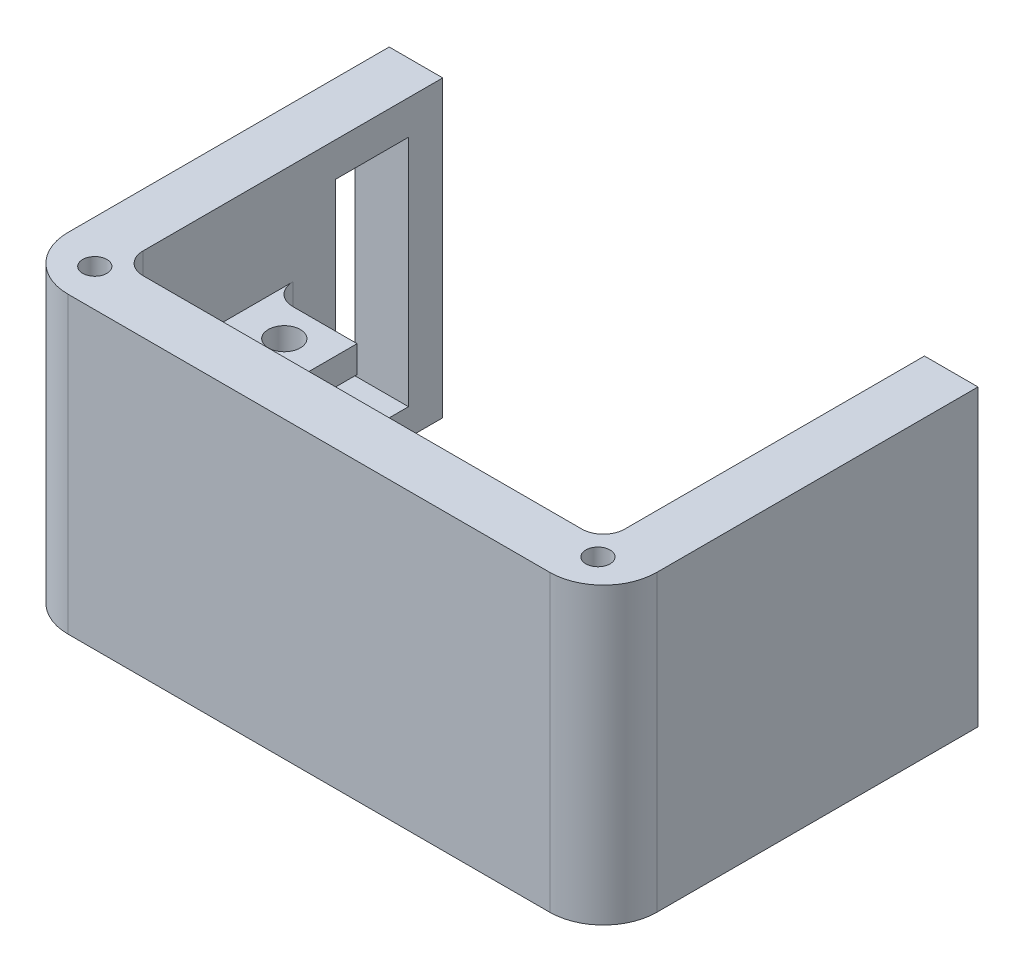
SolidWorks part; units mm, degrees
ref_plane "Front Plane" through (0, 0, 0) normal (0, 0, 1) x (1, 0, 0)
ref_plane "Top Plane" through (0, 0, 0) normal (0, 1, 0) x (1, 0, 0)
ref_plane "Right Plane" through (0, 0, 0) normal (1, 0, 0) x (0, 0, -1)
sketch "Sketch1" plane through (0, 0, 0) normal (0, 1, 0) x (1, 0, 0)
  line L0 (0, -55) -> (0, 55) construction
  line L1 (-34.925, -15.875) -> (34.925, -15.875)
  line L2 (-34.925, -15.875) -> (-34.925, 15.875)
  line L3 (-34.925, 15.875) -> (34.925, 15.875) construction
  line L4 (34.925, -15.875) -> (34.925, 15.875)
  line L5 (-34.925, -15.875) -> (34.925, 15.875) construction
  line L6 (-34.925, 15.875) -> (34.925, -15.875) construction
  line L7 (28.575, 15.875) -> (-28.575, 15.875) construction
  line L8 (28.575, 15.875) -> (28.575, -9.525)
  line L9 (28.575, -9.525) -> (-28.575, -9.525)
  line L10 (-28.575, 15.875) -> (-28.575, -9.525)
  line L11 (28.575, 15.875) -> (-28.575, -9.525) construction
  line L12 (28.575, -9.525) -> (-28.575, 15.875) construction
  line L13 (-28.575, 15.875) -> (-34.925, 15.875)
  line L14 (34.925, 15.875) -> (34.925, 28.575)
  line L15 (34.925, 28.575) -> (28.575, 28.575)
  line L16 (28.575, 28.575) -> (28.575, 15.875)
  point P0 (0, 0)
  point P6 (0, 3.175)
  point P11 (0, -9.525)
  dimension "D1" = 31.75
  dimension "D2" = 69.85
  dimension "D3" = 57.15
  dimension "D4" = 25.4
  dimension "D5" = 44.45
extrude "Boss-Extrude1" add sketch "Sketch1" along normal blind 31.75 contours L10 L3 L2 L1 L4 L8 L9
sketch "Sketch5" plane through (-28.575, 0, 0) normal (1, 0, 0) x (0, 0, -1)
  line L1 (0.635, 16.51) -> (8.255, 16.51)
  line L2 (0.635, 16.51) -> (0.635, 19.685)
  line L3 (0.635, 19.685) -> (8.255, 19.685)
  line L4 (8.255, 16.51) -> (8.255, 19.685)
  line L5 (0.635, 16.51) -> (8.255, 19.685) construction
  line L6 (0.635, 19.685) -> (8.255, 16.51) construction
  line L8 (15.875, 31.75) -> (-9.525, 31.75) construction
  line L10 (15.875, 31.75) -> (15.875, 0) construction
  point P0 (4.445, 18.0975)
  dimension "D1" = 7.62
  dimension "D2" = 3.175
  dimension "D3" = 15.24
  dimension "D4" = 7.62
extrude "Boss-Extrude2" add sketch "Sketch5" along normal blind 10.16 contours L3 L4 L1 L2
sketch "Sketch7" plane through (0, 19.685, 0) normal (0, 1, 0) x (1, 0, 0)
  line L1 (-28.575, 0.635) -> (-28.575, 8.255) construction
  line L3 (-18.415, 0.635) -> (-28.575, 0.635) construction
  point P0 (-23.241, 4.445)
  dimension "D1" = 3.81
  dimension "D2" = 5.334
hole_wizard "#6 Clearance Hole1" positions "Sketch8" profile "Sketch10" hole size "#6" standard "ANSI Inch" end condition up to next
sketch "Sketch8" plane through (0, 19.685, 0) normal (0, 1, 0) x (1, 0, 0)
  point P0 (-23.241, 4.445)
sketch "Sketch10" plane through (-23.241, 19.685, -4.445) normal (1, 0, 0) x (0, 0, 1)
  line L0 (0, 0) -> (0, 3.175)
  line L1 (0, 3.175) -> (1.8986, 3.175)
  line L2 (1.8986, 3.175) -> (1.8986, 0)
  line L5 (1.8986, 0) -> (0, 0)
  line L11 (0, -6.35) -> (0, 107.95) construction
  dimension "Thru Hole Dia." = 3.7973
  dimension "Thru Hole Depth" = 3.175
mirror "Mirror4" about plane through (0, 0, 0) normal (1, 0, 0) of "#6 Clearance Hole1", "Boss-Extrude2"
sketch "Sketch11" plane through (0, 0, 0) normal (0, -1, 0) x (1, 0, 0)
  line L5 (-28.575, -15.875) -> (-28.575, 9.525) construction
  line L7 (-34.925, 15.875) -> (-34.925, -15.875) construction
  line L13 (-28.575, -28.575) -> (-28.575, 9.525)
  line L15 (-34.925, 15.875) -> (-34.925, -28.575)
  line L17 (-34.925, -28.575) -> (-28.575, -28.575)
  line L18 (-28.575, -15.875) -> (-34.925, -15.875) construction
  line L19 (-28.575, 9.525) -> (28.575, 9.525)
  line L20 (28.575, 9.525) -> (28.575, -28.575)
  line L21 (28.575, -28.575) -> (34.925, -28.575)
  line L22 (34.925, -28.575) -> (34.925, 15.875)
  line L23 (34.925, 15.875) -> (-34.925, 15.875)
  dimension "D1" = 12.7
extrude "Boss-Extrude3" add sketch "Sketch11" along normal blind 3.175 contours L15 L17 L13 L19 L20 L21 L22 L23
sketch "Sketch12" [suppressed] plane through (0, 0, 0) normal (0, 1, 0) x (1, 0, 0)
  line L0 (-28.575, 28.575) -> (-28.575, 15.875) construction
  line L1 (-34.925, 28.575) -> (-28.575, 28.575)
  line L2 (-34.925, 28.575) -> (-34.925, 24.511)
  line L3 (-34.925, 24.511) -> (-28.575, 24.511)
  line L4 (-28.575, 28.575) -> (-28.575, 24.511)
  dimension "D1" = 4.064
extrude "Boss-Extrude4" [suppressed] add sketch "Sketch12" along normal blind 12.7
fillet "Fillet1" radius 6.35 2 edges at (34.925, 14.2875, 15.875) (-34.925, 14.2875, 15.875)
fillet "Fillet2" radius 2.54 4 edges at (-28.575, 18.0975, -0.635) (-28.575, 18.0975, -8.255) (28.575, 18.0975, -0.635) (28.575, 18.0975, -8.255)
fillet "Fillet3" radius 2.54 2 edges at (-28.575, 16.51, -4.445) (28.575, 16.51, -4.445)
fillet "Fillet4" radius 2.54 2 edges at (-28.575, 14.2875, 9.525) (28.575, 14.2875, 9.525)
sketch "Sketch13" plane through (0, 31.75, 0) normal (0, 1, 0) x (1, 0, 0)
  line L0 (28.575, 28.575) -> (28.575, -6.985) construction
  line L2 (26.035, -9.525) -> (-26.035, -9.525) construction
  line L3 (29.845, -11.43) -> (-29.845, -11.43) construction
  line L4 (0, -17.4625) -> (0, 17.4625) construction
  point P0 (29.845, -11.43)
  point P1 (-29.845, -11.43)
  point P2 (0, -11.43)
  dimension "D1" = 1.27
  dimension "D3" = 1.905
hole_wizard "#6-40 Tapped Hole1" positions "Sketch14" profile "Sketch16" tap size "#6-40" standard "ANSI Inch"
sketch "Sketch14" plane through (0, 31.75, 0) normal (0, 1, 0) x (1, 0, 0)
  point P0 (29.845, -11.43)
  point P3 (-29.845, -11.43)
cosmetic thread "Hole Thread1" parameters "D1"=35.052, "D2"=3.5052
cosmetic thread "Hole Thread2" parameters "D1"=35.052, "D2"=3.5052
sketch "Sketch16" plane through (29.845, 31.75, 11.43) normal (1, 0, 0) x (0, 0, 1)
  line L0 (0, 0) -> (0, 38.9623)
  line L1 (0, 38.9623) -> (1.4351, 38.1)
  line L2 (1.4351, 38.1) -> (1.4351, 0)
  line L5 (1.4351, 0) -> (0, 0)
  line L10 (0, 38.9623) -> (-1.4351, 38.1) construction
  line L11 (0, -6.35) -> (0, 107.95) construction
  dimension "Tap Drill Dia." = 2.8702
  dimension "Tap Drill Depth" = 38.1
  dimension "Drill Angle" = 118
sketch "Sketch17" plane through (-34.925, 0, 0) normal (-1, 0, 0) x (0, 0, 1)
  line L0 (-28.575, 0) -> (-28.575, 31.75)
  line L1 (-28.575, 31.75) -> (-15.875, 31.75)
  line L2 (24.4475, 0) -> (-24.4475, 0) construction
  line L3 (-28.575, 0) -> (-24.511, 0)
  line L4 (-24.511, 0) -> (-24.511, 27.686)
  line L5 (-24.511, 27.686) -> (-15.875, 27.686)
  line L6 (-15.875, 31.75) -> (-15.875, 0) construction
  line L7 (-15.875, 27.686) -> (-15.875, 31.75)
  dimension "D1" = 4.064
  dimension "D2" = 4.064
extrude "Boss-Extrude5" add sketch "Sketch17" against normal up to surface (6.35 mm away) up to face at (-28.575, 16.8275, -4.445)
